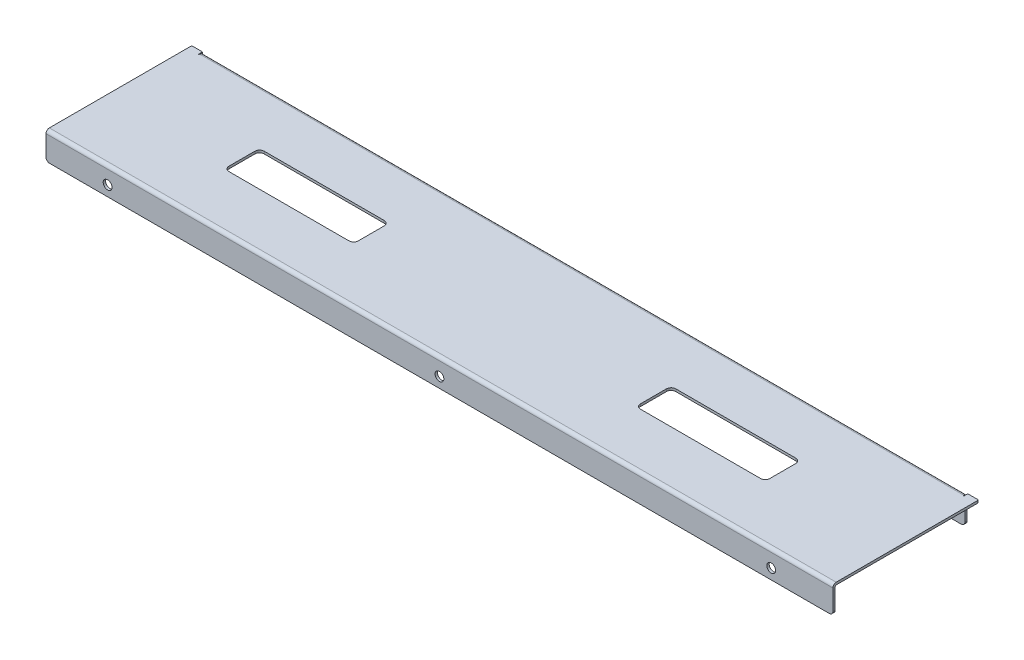
SolidWorks part; units mm, degrees
ref_plane "Front Plane" through (0, 0, 0) normal (0, 0, 1) x (1, 0, 0)
ref_plane "Top Plane" through (0, 0, 0) normal (0, 1, 0) x (1, 0, 0)
ref_plane "Right Plane" through (0, 0, 0) normal (1, 0, 0) x (0, 0, -1)
ref_plane "Plane1" through (0, 290.0934, 0) normal (0, -1, 0) x (1, 0, 0)
sketch "Sketch1" plane through (0, 290.0934, 0) normal (0, -1, 0) x (1, 0, 0)
  line L0 (426.4406, 80.2386) -> (1.5494, 80.2386)
  line L1 (1.5494, 80.2386) -> (1.5494, 78.9432)
  line L2 (1.5494, 78.9432) -> (1.5494, 78.4352)
  line L3 (1.5494, 78.4352) -> (1.5494, 3.6576)
  line L4 (1.5494, 3.6576) -> (426.4406, 3.6576)
  line L5 (426.4406, 3.6576) -> (426.4406, 78.4352)
  line L6 (426.4406, 78.4352) -> (426.4406, 78.9432)
  line L7 (426.4406, 78.9432) -> (426.4406, 80.2386)
extrude "Boss-Extrude1" add sketch "Sketch1" against normal blind 12.9032
sketch "Sketch2" plane through (0, 302.9966, 0) normal (0, 1, 0) x (-1, 0, 0)
  line L0 (-1.5494, 3.6576) -> (-426.4406, 3.6576)
  line L1 (-426.4406, 3.6576) -> (-426.4406, 78.4352)
  line L2 (-426.4406, 78.4352) -> (-426.4406, 78.9432)
  line L3 (-426.4406, 78.9432) -> (-426.4406, 80.2386)
  line L4 (-426.4406, 80.2386) -> (-1.5494, 80.2386)
  line L5 (-1.5494, 80.2386) -> (-1.5494, 78.9432)
  line L6 (-1.5494, 78.9432) -> (-1.5494, 78.4352)
  line L7 (-1.5494, 78.4352) -> (-1.5494, 3.6576)
extrude "Boss-Extrude2" add sketch "Sketch2" along normal blind 0.508
sketch "Sketch3" plane through (0, 290.0934, 0) normal (0, -1, 0) x (1, 0, 0)
  line L0 (1.5494, 3.6576) -> (426.4406, 3.6576)
  line L1 (426.4406, 3.6576) -> (426.4406, 78.4352)
  line L2 (426.4406, 78.4352) -> (426.4406, 78.9432)
  line L3 (426.4406, 78.9432) -> (1.5494, 78.9432)
  line L4 (1.5494, 78.9432) -> (1.5494, 78.4352)
  line L5 (1.5494, 78.4352) -> (1.5494, 3.6576)
extrude "Cut-Extrude1" cut sketch "Sketch3" against normal blind 12.9032
sketch "Sketch4" plane through (0, 303.5046, 0) normal (0, 1, 0) x (-1, 0, 0)
  line L0 (-1.5494, 3.6576) -> (-426.4406, 3.6576)
  line L1 (-426.4406, 3.6576) -> (-426.4406, 78.4352)
  line L2 (-426.4406, 78.4352) -> (-426.4406, 80.2386)
  line L3 (-426.4406, 80.2386) -> (-1.5494, 80.2386)
  line L4 (-1.5494, 80.2386) -> (-1.5494, 78.4352)
  line L5 (-1.5494, 78.4352) -> (-1.5494, 3.6576)
extrude "Boss-Extrude3" add sketch "Sketch4" along normal blind 1.2954
sketch "Sketch5" plane through (0, 302.9966, 0) normal (0, -1, 0) x (1, 0, 0)
  line L0 (1.5494, 3.6576) -> (426.4406, 3.6576)
  line L1 (426.4406, 3.6576) -> (426.4406, 78.4352)
  line L2 (426.4406, 78.4352) -> (426.4406, 78.9432)
  line L3 (426.4406, 78.9432) -> (1.5494, 78.9432)
  line L4 (1.5494, 78.9432) -> (1.5494, 78.4352)
  line L5 (1.5494, 78.4352) -> (1.5494, 3.6576)
extrude "Cut-Extrude2" cut sketch "Sketch5" against normal blind 0.508
sketch "Sketch6" plane through (0, 0, 3.6576) normal (0, 0, -1) x (-1, 0, 0)
  line L0 (-420.3192, 302.9966) -> (-420.3192, 303.5046)
  line L1 (-420.3192, 303.5046) -> (-420.3192, 304.8)
  line L2 (-420.3192, 304.8) -> (-7.6708, 304.8)
  line L3 (-7.6708, 304.8) -> (-7.6708, 303.5046)
  line L4 (-7.6708, 303.5046) -> (-7.6708, 302.9966)
  line L5 (-7.6708, 302.9966) -> (-420.3192, 302.9966)
extrude "Boss-Extrude4" add sketch "Sketch6" along normal blind 0.3048
sketch "Sketch7" plane through (0, 0, 3.3528) normal (0, 0, -1) x (-1, 0, 0)
  line L0 (-420.3192, 302.9966) -> (-420.3192, 303.5046)
  line L1 (-420.3192, 303.5046) -> (-420.3192, 304.8)
  line L2 (-420.3192, 304.8) -> (-7.6708, 304.8)
  line L3 (-7.6708, 304.8) -> (-7.6708, 303.5046)
  line L4 (-7.6708, 303.5046) -> (-7.6708, 302.9966)
  line L5 (-7.6708, 302.9966) -> (-420.3192, 302.9966)
extrude "Boss-Extrude5" add sketch "Sketch7" along normal blind 0.508
sketch "Sketch8" plane through (0, 0, 3.6576) normal (0, 0, 1) x (1, 0, 0)
  line L0 (7.6708, 302.9966) -> (420.3192, 302.9966)
  line L1 (420.3192, 302.9966) -> (420.3192, 303.5046)
  line L2 (420.3192, 303.5046) -> (7.6708, 303.5046)
  line L3 (7.6708, 303.5046) -> (7.6708, 302.9966)
extrude "Cut-Extrude3" cut sketch "Sketch8" against normal blind 0.3048
sketch "Sketch9" plane through (0, 0, 2.8448) normal (0, 0, -1) x (-1, 0, 0)
  line L0 (-420.3192, 302.9966) -> (-420.3192, 304.8)
  line L1 (-420.3192, 304.8) -> (-7.6708, 304.8)
  line L2 (-7.6708, 304.8) -> (-7.6708, 302.9966)
  line L3 (-7.6708, 302.9966) -> (-420.3192, 302.9966)
extrude "Boss-Extrude6" add sketch "Sketch9" along normal blind 1.2954
sketch "Sketch10" plane through (0, 0, 3.3528) normal (0, 0, 1) x (1, 0, 0)
  line L0 (7.6708, 302.9966) -> (420.3192, 302.9966)
  line L1 (420.3192, 302.9966) -> (420.3192, 303.5046)
  line L2 (420.3192, 303.5046) -> (7.6708, 303.5046)
  line L3 (7.6708, 303.5046) -> (7.6708, 302.9966)
extrude "Cut-Extrude4" cut sketch "Sketch10" against normal blind 0.508
sketch "Sketch11" plane through (0, 302.9966, 0) normal (0, -1, 0) x (1, 0, 0)
  line L0 (420.3192, 1.5494) -> (7.6708, 1.5494)
  line L1 (7.6708, 1.5494) -> (7.6708, 2.8448)
  line L2 (7.6708, 2.8448) -> (420.3192, 2.8448)
  line L3 (420.3192, 2.8448) -> (420.3192, 1.5494)
extrude "Boss-Extrude7" add sketch "Sketch11" along normal blind 12.9032
sketch "Sketch12" plane through (0, 0, 3.6576) normal (0, 0, -1) x (-1, 0, 0)
  line L0 (-7.366, 304.8) -> (-1.5494, 304.8)
  line L1 (-1.5494, 304.8) -> (-1.5494, 303.5046)
  line L2 (-1.5494, 303.5046) -> (-7.366, 303.5046)
  line L3 (-7.366, 303.5046) -> (-7.366, 304.8)
extrude "Boss-Extrude8" add sketch "Sketch12" along normal blind 2.1082
sketch "Sketch13" plane through (0, 0, 3.6576) normal (0, 0, -1) x (-1, 0, 0)
  line L0 (-426.4406, 304.8) -> (-420.624, 304.8)
  line L1 (-420.624, 304.8) -> (-420.624, 303.5046)
  line L2 (-420.624, 303.5046) -> (-426.4406, 303.5046)
  line L3 (-426.4406, 303.5046) -> (-426.4406, 304.8)
extrude "Boss-Extrude9" add sketch "Sketch13" along normal blind 2.1082
hole_wizard "Hole1" positions "Sketch15" profile "Sketch14" legacy
sketch "Sketch15" plane through (0, 0, 1.5494) normal (0, 0, -1) x (-1, 0, 0)
  point P0 (-213.995, 295.9989)
  point P1 (-393.1666, 295.9989)
  point P2 (-34.8234, 295.9989)
sketch "Sketch14" plane through (213.995, 295.9989, 1.5494) normal (1, 0, 0) x (0, 1, 0)
  line L0 (0, 0) -> (0, 1.2954)
  line L1 (0, 1.2954) -> (2.4765, 1.2954)
  line L2 (2.4765, 1.2954) -> (2.4765, 0)
  line L3 (2.4765, 0) -> (0, 0)
  line L4 (0, 110) -> (0, -10) construction
  dimension "Diameter" = 4.953
  dimension "Depth" = 1.2954
hole_wizard "3/16 (0.1875) Diameter Hole1" positions "Sketch17" profile "Sketch16" hole size "3/16" standard "ANSI Inch"
sketch "Sketch17" plane through (0, 0, 80.2386) normal (0, 0, 1) x (1, 0, 0)
  point P0 (34.8234, 295.6878)
  point P1 (213.995, 295.6878)
  point P2 (393.1666, 295.6878)
sketch "Sketch16" plane through (34.8234, 295.6878, 80.2386) normal (1, 0, 0) x (0, -1, 0)
  line L0 (0, 0) -> (0, 78.6892)
  line L1 (0, 78.6892) -> (2.3812, 78.6892)
  line L2 (2.3812, 78.6892) -> (2.3812, 0)
  line L5 (2.3812, 0) -> (0, 0)
  line L11 (0, -6.35) -> (0, 107.95) construction
  dimension "Thru Hole Dia." = 4.7625
  dimension "Thru Hole Depth" = 78.6892
fillet "Fillet1" radius 0.508 4 edges at (426.4406, 304.1523, 1.5494) (213.995, 303.5046, 2.8448) (1.5494, 304.1523, 1.5494) (213.995, 303.5046, 78.9432)
fillet "Fillet2" radius 1.8034 2 edges at (213.995, 304.8, 80.2386) (213.995, 304.8, 1.5494)
fillet "Fillet3" radius 1.905 4 edges at (420.3192, 290.0934, 2.1971) (1.5494, 290.0934, 79.5909) (7.6708, 290.0934, 2.1971) (426.4406, 290.0934, 79.5909)
sketch "Sketch18" plane through (0, 303.5046, 0) normal (0, -1, 0) x (1, 0, 0)
  line L0 (9.5758, 1.5494) -> (418.4142, 1.5494) construction
  line L1 (357.505, 50.3682) -> (292.735, 50.3682)
  line L2 (360.045, 47.8282) -> (360.045, 33.8582)
  line L3 (357.505, 31.3182) -> (292.735, 31.3182)
  line L4 (290.195, 47.8282) -> (290.195, 33.8582)
  line L5 (1.5494, 78.9432) -> (426.4406, 78.9432) construction
  line L6 (213.995, 3.3528) -> (213.995, 78.4352) construction
  line L7 (7.6708, 3.3528) -> (420.3192, 3.3528) construction
  line L8 (426.4406, 78.4352) -> (1.5494, 78.4352) construction
  line L9 (137.795, 47.8282) -> (137.795, 33.8582)
  line L10 (70.485, 31.3182) -> (135.255, 31.3182)
  line L11 (67.945, 47.8282) -> (67.945, 33.8582)
  line L12 (70.485, 50.3682) -> (135.255, 50.3682)
  arc A0 (292.735, 50.3682) -> (290.195, 47.8282) centre (292.735, 47.8282) ccw
  arc A1 (292.735, 31.3182) -> (290.195, 33.8582) centre (292.735, 33.8582) cw
  arc A2 (360.045, 33.8582) -> (357.505, 31.3182) centre (357.505, 33.8582) cw
  arc A3 (357.505, 50.3682) -> (360.045, 47.8282) centre (357.505, 47.8282) cw
  arc A4 (70.485, 50.3682) -> (67.945, 47.8282) centre (70.485, 47.8282) ccw
  arc A5 (67.945, 33.8582) -> (70.485, 31.3182) centre (70.485, 33.8582) ccw
  arc A6 (135.255, 31.3182) -> (137.795, 33.8582) centre (135.255, 33.8582) ccw
  arc A7 (135.255, 50.3682) -> (137.795, 47.8282) centre (135.255, 47.8282) cw
  point P6 (213.995, 1.5494)
  point P7 (360.045, 40.8432)
  point P14 (290.195, 31.3182)
  point P17 (360.045, 31.3182)
  point P20 (360.045, 50.3682)
  point P39 (67.945, 50.3682)
  point P40 (67.945, 31.3182)
  point P41 (137.795, 31.3182)
  dimension "D5" = 2.54
  dimension "D1" = 76.2
  dimension "D2" = 69.85
  dimension "D3" = 19.05
  dimension "D4" = 38.1
extrude "Cut-Extrude5" cut sketch "Sketch18" against normal through all
